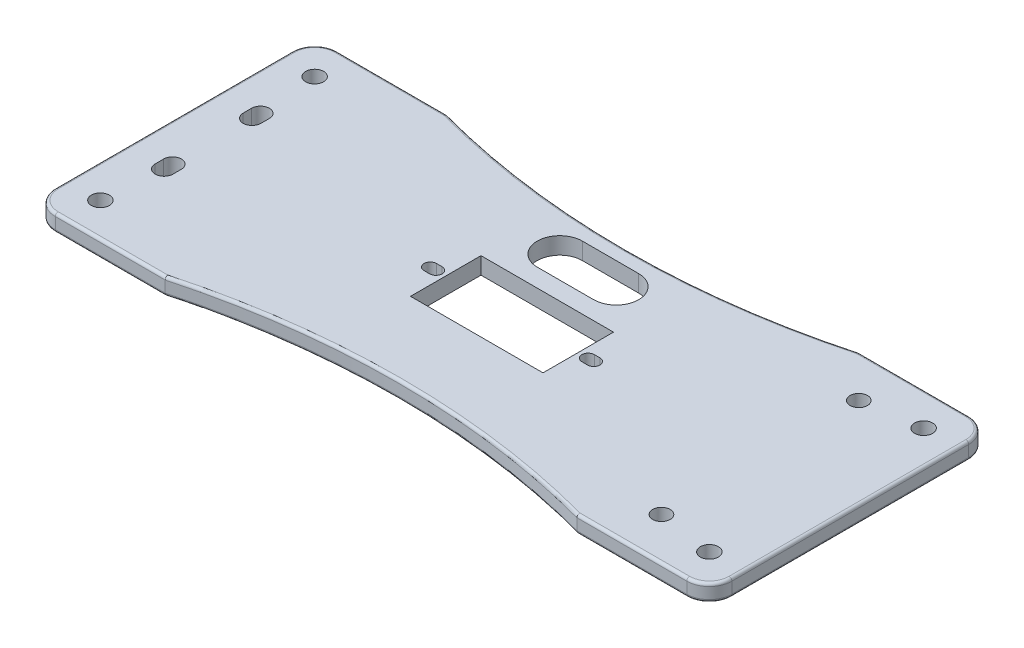
SolidWorks part; units mm, degrees
ref_plane "Front Plane" through (0, 0, 0) normal (0, 0, 1) x (1, 0, 0)
ref_plane "Top Plane" through (0, 0, 0) normal (0, 1, 0) x (1, 0, 0)
ref_plane "Right Plane" through (0, 0, 0) normal (1, 0, 0) x (0, 0, -1)
sketch "Sketch1" plane through (0, 0, 0) normal (0, 1, 0) x (1, 0, 0)
  line L1 (-60, -25) -> (60, -25)
  line L2 (-60, -25) -> (-60, 25)
  line L3 (-60, 25) -> (60, 25)
  line L4 (60, -25) -> (60, 25)
  line L5 (-60, -25) -> (60, 25) construction
  line L6 (-60, 25) -> (60, -25) construction
  line L7 (54, -19) -> (-54, -19) construction
  line L8 (54, -19) -> (54, 19) construction
  line L9 (54, 19) -> (-54, 19) construction
  line L10 (-54, -19) -> (-54, 19) construction
  line L11 (54, -19) -> (-54, 19) construction
  line L12 (54, 19) -> (-54, -19) construction
  circle A0 centre (-54, 19) radius 1.6
  circle A1 centre (54, 19) radius 1.6
  circle A2 centre (54, -19) radius 1.6
  circle A3 centre (-54, -19) radius 1.6
  point P0 (0, 0)
  point P6 (0, 0)
  dimension "D5" = 3.2
  dimension "D1" = 120
  dimension "D2" = 50
  dimension "D3" = 108
  dimension "D4" = 38
extrude "Boss-Extrude1" add sketch "Sketch1" along normal blind 3
sketch "Sketch2" plane through (0, 3, 0) normal (0, 1, 0) x (1, 0, 0)
  line L0 (0, 0) -> (-57.6652, 0) construction
  line L1 (-53.1568, 7.05) -> (-53.1568, 8.55) construction
  line L2 (-54.7318, 7.05) -> (-54.7318, 8.55)
  line L3 (-51.5818, 7.05) -> (-51.5818, 8.55)
  line L4 (-53.1568, -7.05) -> (-53.1568, -8.55) construction
  line L5 (-51.5818, -7.05) -> (-51.5818, -8.55)
  line L6 (-54.7318, -7.05) -> (-54.7318, -8.55)
  line L7 (0, -6.25) -> (0, 6.25) construction
  line L8 (-11.75, -6.25) -> (11.75, -6.25)
  line L9 (-11.75, -6.25) -> (-11.75, 6.25)
  line L10 (-11.75, 6.25) -> (11.75, 6.25)
  line L11 (11.75, -6.25) -> (11.75, 6.25)
  line L12 (-11.75, -6.25) -> (11.75, 6.25) construction
  line L13 (-11.75, 6.25) -> (11.75, -6.25) construction
  line L14 (-14.5, 0) -> (-13.5, 0) construction
  line L15 (-5, 13.477) -> (5, 13.477) construction
  line L16 (-5, 17.477) -> (5, 17.477)
  line L17 (-5, 9.477) -> (5, 9.477)
  line L18 (-14.5, 1.1) -> (-13.5, 1.1)
  line L19 (-14.5, -1.1) -> (-13.5, -1.1)
  line L22 (0, 0) -> (55.6599, 0) construction
  line L23 (13.5, 0) -> (14.5, 0) construction
  line L24 (13.5, 1.1) -> (14.5, 1.1)
  line L25 (13.5, -1.1) -> (14.5, -1.1)
  line L26 (-14, 1.1) -> (-14, 9.8464) construction
  line L27 (14, 1.1) -> (14, 9.8464) construction
  arc A2 (-54.7318, 7.05) -> (-51.5818, 7.05) centre (-53.1568, 7.05) ccw
  arc A3 (-51.5818, 8.55) -> (-54.7318, 8.55) centre (-53.1568, 8.55) ccw
  arc A4 (-51.5818, -7.05) -> (-54.7318, -7.05) centre (-53.1568, -7.05) ccw
  arc A5 (-54.7318, -8.55) -> (-51.5818, -8.55) centre (-53.1568, -8.55) ccw
  arc A8 (-5, 17.477) -> (-5, 9.477) centre (-5, 13.477) ccw
  arc A9 (5, 9.477) -> (5, 17.477) centre (5, 13.477) ccw
  circle A11 centre (44, 17.5) radius 1.55
  circle A12 centre (44, -17.5) radius 1.55
  circle A13 centre (54, 19) radius 1.6 construction
  arc A14 (-14.5, 1.1) -> (-14.5, -1.1) centre (-14.5, 0) ccw
  arc A15 (-13.5, -1.1) -> (-13.5, 1.1) centre (-13.5, 0) ccw
  arc A16 (13.5, 1.1) -> (13.5, -1.1) centre (13.5, 0) ccw
  arc A17 (14.5, -1.1) -> (14.5, 1.1) centre (14.5, 0) ccw
  circle A18 centre (-14, 9.8464) radius 1.4391 construction
  circle A19 centre (14, 9.8464) radius 1.4391 construction
  point P5 (-53.1568, 7.8)
  point P11 (-53.1568, -7.8)
  point P17 (0, 0)
  point P23 (-14, 0)
  point P30 (0, 13.477)
  point P41 (14, 0)
  point P58 (0, 0)
  point P59 (0, 17.5)
  point P60 (0, 13.477)
  dimension "D1" = 1.575
  dimension "D7" = 1.1
  dimension "D9" = 4
  dimension "D11" = 3.1
  dimension "D13" = 35
  dimension "D6" = 28
  dimension "D2" = 1.5
  dimension "D3" = 15.6
  dimension "D4" = 12.5
  dimension "D5" = 23.5
  dimension "D8" = 1
  dimension "D10" = 10
  dimension "D12" = 10
extrude "Cut-Extrude1" cut sketch "Sketch2" against normal blind 10
sketch "Sketch4" plane through (0, 3, 0) normal (0, 1, 0) x (1, 0, 0)
  line L1 (0, -160.1582) -> (0, 0) construction
  line L2 (-60, -25) -> (60, -25) construction
  line L3 (-36.5, -25) -> (36.5, -25)
  line L4 (-11.75, 0) -> (11.75, 0) construction
  line L5 (-11.75, 6.25) -> (-11.75, -6.25) construction
  line L6 (11.75, -6.25) -> (11.75, 6.25) construction
  line L7 (-36.5, 25) -> (36.5, 25)
  arc A0 (36.5, -25) -> (-36.5, -25) centre (0, -160.1582) ccw
  arc A1 (36.5, 25) -> (-36.5, 25) centre (0, 160.1582) cw
  dimension "D1" = 140
  dimension "D2" = 73
extrude "Cut-Extrude2" cut sketch "Sketch4" against normal blind 10
fillet "Fillet1" radius 4 4 edges at (-60, 1.5, 25) (60, 1.5, 25) (-60, 1.5, -25) (60, 1.5, -25)
fillet "Fillet2" radius 0.5 26 edges at (-58.8284, 0, 23.8284) (-60, 0, 0) (-58.8284, 0, -23.8284) (-46.25, 0, -25) (46.25, 0, -25) (58.8284, 0, -23.8284) (60, 0, 0) (58.8284, 0, 23.8284) (-58.8284, 3, 23.8284) (-60, 3, 0) (-58.8284, 3, -23.8284) (46.25, 3, -25) (-46.25, 3, -25) (58.8284, 3, -23.8284) (60, 3, 0) (58.8284, 3, 23.8284) (-46.25, 0, 25) (46.25, 0, 25) (-46.25, 3, 25) (46.25, 3, 25) (-36.5, 1.5, -25) (36.5, 1.5, -25) (0, 3, -20.1582) (0, 0, -20.1582) (0, 0, 20.1582) (0, 3, 20.1582)
